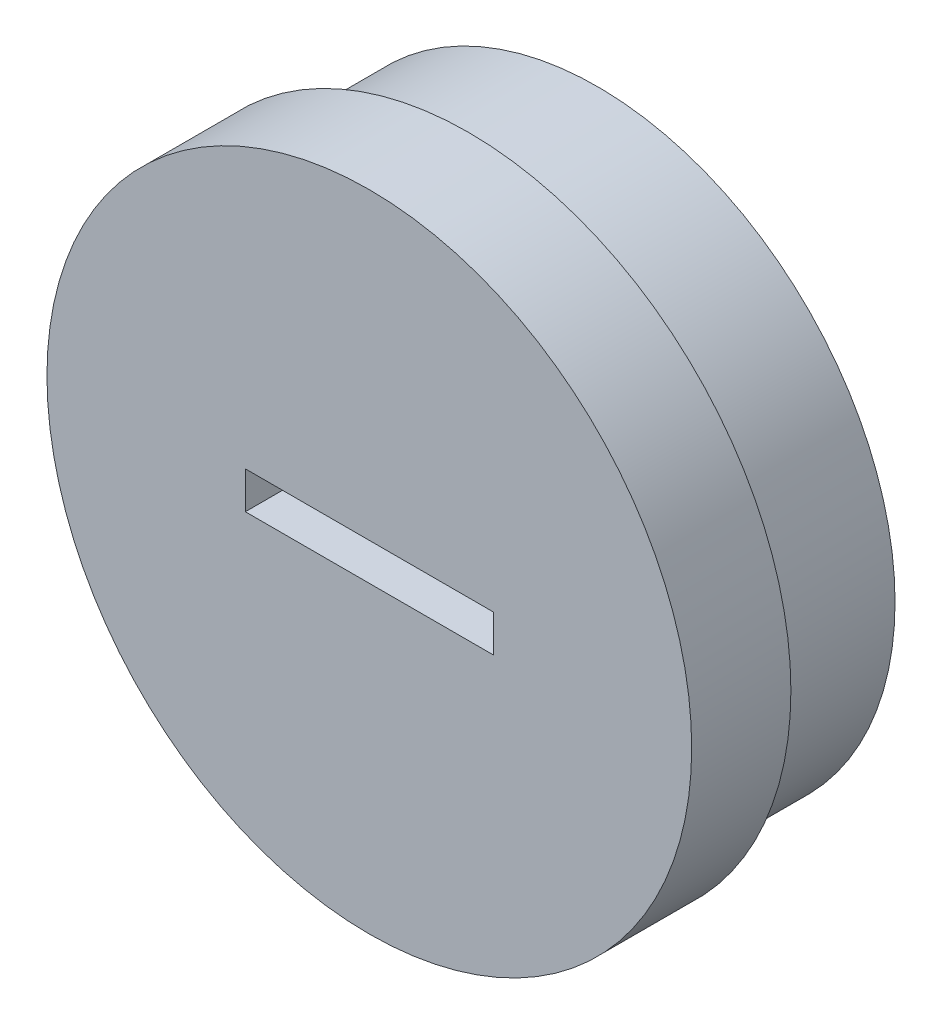
SolidWorks part; units mm, degrees
ref_plane "정면" through (0, 0, 0) normal (0, 0, 1) x (1, 0, 0)
ref_plane "윗면" through (0, 0, 0) normal (0, 1, 0) x (1, 0, 0)
ref_plane "우측면" through (0, 0, 0) normal (1, 0, 0) x (0, 0, -1)
sketch "스케치1" plane through (0, 0, 0) normal (0, 0, 1) x (1, 0, 0)
  circle A0 centre (0, 0) radius 13
  dimension "D1" = 26
extrude "보스-돌출1" add sketch "스케치1" along normal blind 4
sketch "스케치2" plane through (0, 0, 0) normal (0, 0, 1) x (1, 0, 0)
  circle A0 centre (0, 0) radius 12
  circle A1 centre (0, 0) radius 10.075
  dimension "D1" = 24
  dimension "D2" = 20.15
extrude "보스-돌출2" add sketch "스케치2" against normal blind 5.2
sketch "스케치3" plane through (0, 0, 4) normal (0, 0, 1) x (1, 0, 0)
  line L1 (-5, 0.75) -> (5, 0.75)
  line L2 (-5, 0.75) -> (-5, -0.75)
  line L3 (-5, -0.75) -> (5, -0.75)
  line L4 (5, 0.75) -> (5, -0.75)
  line L5 (-5, 0.75) -> (5, -0.75) construction
  line L6 (-5, -0.75) -> (5, 0.75) construction
  point P0 (0, 0)
  dimension "D1" = 1.5
  dimension "D2" = 10
extrude "컷-돌출1" cut sketch "스케치3" against normal blind 2.5
